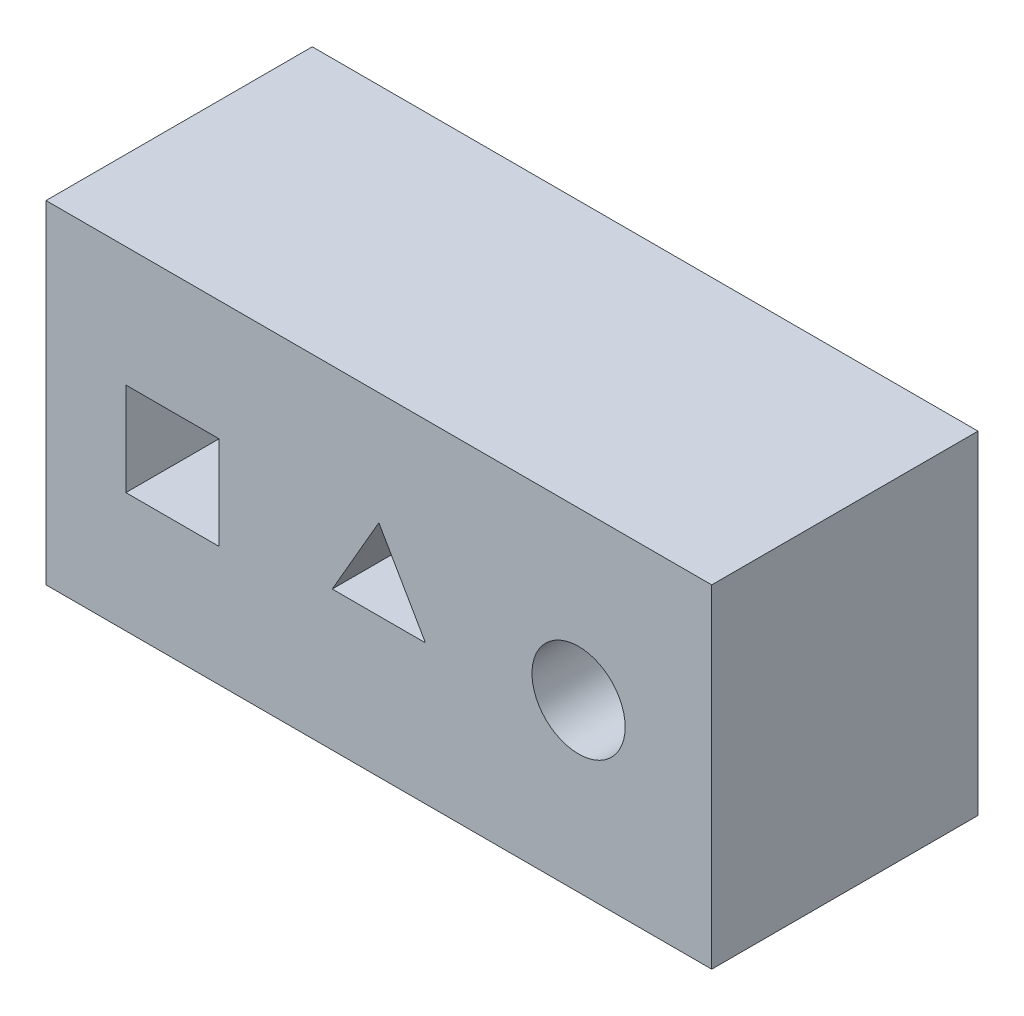
SolidWorks part; units mm, degrees
ref_plane "Front Plane" through (0, 0, 0) normal (0, 0, 1) x (1, 0, 0)
ref_plane "Top Plane" through (0, 0, 0) normal (0, 1, 0) x (1, 0, 0)
ref_plane "Right Plane" through (0, 0, 0) normal (1, 0, 0) x (0, 0, -1)
sketch "Sketch1" plane through (0, 0, 0) normal (0, 0, 1) x (1, 0, 0)
  line L1 (125, -62.5) -> (-125, -62.5)
  line L2 (125, -62.5) -> (125, 62.5)
  line L3 (125, 62.5) -> (-125, 62.5)
  line L4 (-125, -62.5) -> (-125, 62.5)
  line L5 (125, -62.5) -> (-125, 62.5) construction
  line L6 (125, 62.5) -> (-125, -62.5) construction
  line L7 (115, -57.5) -> (-115, -57.5)
  line L8 (115, -57.5) -> (115, 57.5)
  line L9 (115, 57.5) -> (-115, 57.5)
  line L10 (-115, -57.5) -> (-115, 57.5)
  line L11 (115, -57.5) -> (-115, 57.5) construction
  line L12 (115, 57.5) -> (-115, -57.5) construction
  point P0 (0, 0)
  point P6 (0, 0)
  dimension "D1" = 250
  dimension "D2" = 125
  dimension "D3" = 230
extrude "Boss-Extrude1" add sketch "Sketch1" along normal blind 100
sketch "Sketch2" plane through (0, 0, 0) normal (0, 0, -1) x (-1, 0, 0)
  line L1 (125, 62.5) -> (-125, 62.5)
  line L2 (125, 62.5) -> (125, -62.5)
  line L3 (125, -62.5) -> (-125, -62.5)
  line L4 (-125, 62.5) -> (-125, -62.5)
sketch "Sketch3" plane through (0, 0, 100) normal (0, 0, 1) x (1, 0, 0)
  line L0 (-125, 0) -> (125, 0) construction
  line L1 (-125, 62.5) -> (125, 62.5)
  line L2 (-125, 62.5) -> (-125, -62.5)
  line L3 (-125, -62.5) -> (125, -62.5)
  line L4 (125, 62.5) -> (125, -62.5)
  line L5 (0, 62.5) -> (0, -62.5) construction
  line L6 (-17.5, -10.1036) -> (0, 20.2073)
  line L7 (-95, 17.5) -> (-60, 17.5)
  line L8 (-95, 17.5) -> (-95, -17.5)
  line L9 (-95, -17.5) -> (-60, -17.5)
  line L10 (-60, 17.5) -> (-60, -17.5)
  line L11 (-95, 17.5) -> (-60, -17.5) construction
  line L12 (-95, -17.5) -> (-60, 17.5) construction
  line L14 (-1.3522, 0) -> (0, -1.3522)
  line L18 (0, 20.2073) -> (17.5, -10.1036)
  line L19 (17.5, -10.1036) -> (-17.5, -10.1036)
  line L20 (-17.5, -10.1036) -> (8.75, 5.0518) construction
  line L21 (17.5, -10.1036) -> (-8.75, 5.0518) construction
  line L22 (0, 20.2073) -> (0, 0) construction
  circle A0 centre (75, 0) radius 17.5
  point P10 (-77.5, 0)
  point P20 (0, 0)
  point P27 (7.7505, -5.3087)
  point P28 (0, 0)
  line M21 (-125, 62.5) -> (-125, -62.5)
  line M22 (-125, -62.5) -> (125, -62.5)
  line M23 (125, -62.5) -> (125, 62.5)
  line M24 (125, 62.5) -> (-125, 62.5)
  line M25 (115, -57.5) -> (-115, -57.5)
  line M26 (-115, -57.5) -> (-115, 57.5)
  line M27 (-115, 57.5) -> (115, 57.5)
  line M28 (115, 57.5) -> (115, -57.5)
  dimension "D2" = 50
  dimension "cylinder" = 35
  dimension "D1" = 30
  dimension "square2" = 35
  dimension "square" = 35
  dimension "triangle3" = 35
  dimension "triangle2" = 35
  dimension "triangle" = 35
extrude "Boss-Extrude4" add sketch "Sketch3" against normal up to surface (100 mm away) contours A0 L7 L10 L9 L8 L18 L19 L6 M25 M28 M27 M26 | M24 M21 M22 M23 M28 M25 M26 M27 up to face at (0, 0, 0)
